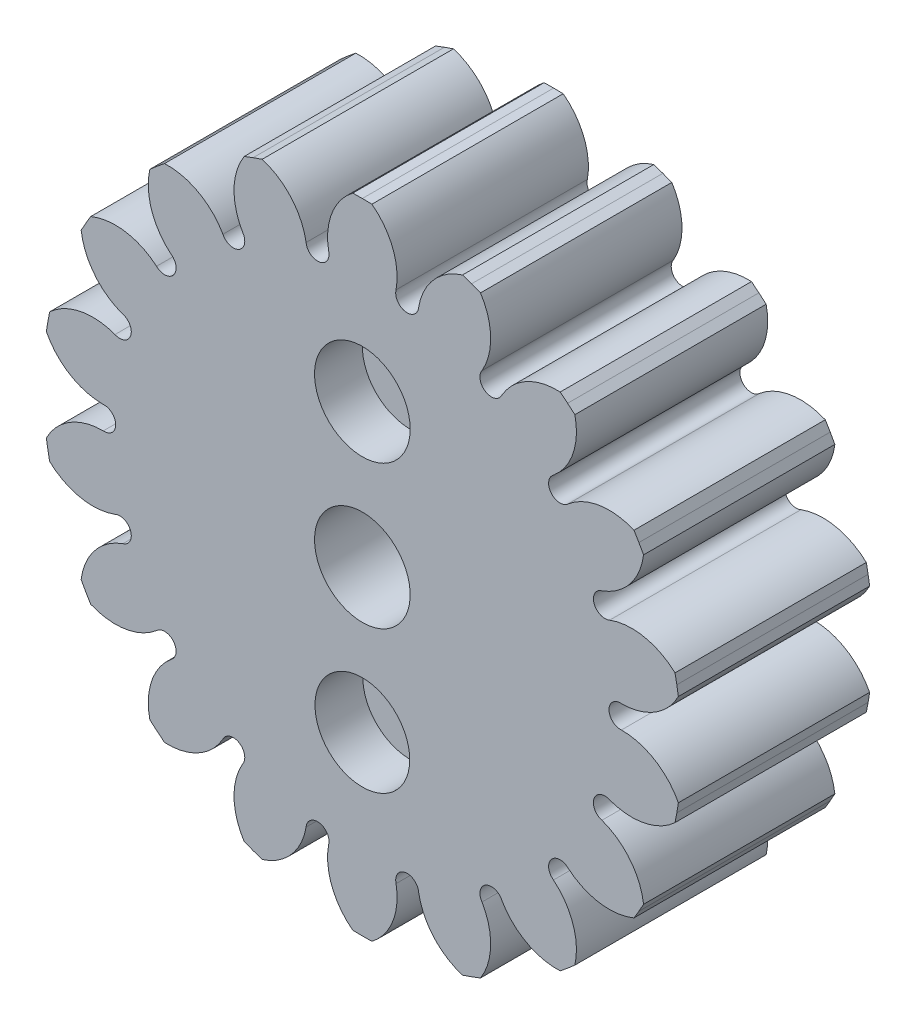
SolidWorks part; units mm, degrees
ref_plane "Front Plane" through (0, 0, 0) normal (0, 0, 1) x (1, 0, 0)
ref_plane "Top Plane" through (0, 0, 0) normal (0, 1, 0) x (1, 0, 0)
ref_plane "Right Plane" through (0, 0, 0) normal (1, 0, 0) x (0, 0, -1)
sketch "Sketch1" plane through (0, 0, 0) normal (0, 0, 1) x (1, 0, 0)
  line L0 (0, 42.401) -> (0, 0) construction
  line L1 (0, 42.401) -> (-1.27, 42.382)
  line L2 (0, 42.401) -> (1.27, 42.382)
  line L3 (14.502, 39.8439) -> (13.3021, 40.2604)
  line L4 (14.502, 39.8439) -> (15.6889, 39.3916)
  line L5 (27.2548, 32.481) -> (26.2697, 33.2828)
  line L6 (27.2548, 32.481) -> (28.2155, 31.6501)
  line L7 (36.7203, 21.2005) -> (36.0689, 22.2908)
  line L8 (36.7203, 21.2005) -> (37.3389, 20.0911)
  line L9 (41.7568, 7.3629) -> (41.5175, 8.6103)
  line L10 (41.7568, 7.3629) -> (41.9586, 6.1088)
  line L11 (41.7568, -7.3629) -> (41.9586, -6.1088)
  line L12 (41.7568, -7.3629) -> (41.5175, -8.6103)
  line L13 (36.7203, -21.2005) -> (37.3389, -20.0911)
  line L14 (36.7203, -21.2005) -> (36.0689, -22.2908)
  line L15 (27.2548, -32.481) -> (28.2155, -31.6501)
  line L16 (27.2548, -32.481) -> (26.2697, -33.2828)
  line L17 (14.502, -39.8439) -> (15.6889, -39.3916)
  line L18 (14.502, -39.8439) -> (13.3021, -40.2604)
  line L19 (0, -42.401) -> (1.27, -42.382)
  line L20 (0, -42.401) -> (-1.27, -42.382)
  line L21 (-14.502, -39.8439) -> (-13.3021, -40.2604)
  line L22 (-14.502, -39.8439) -> (-15.6889, -39.3916)
  line L23 (-27.2548, -32.481) -> (-26.2697, -33.2828)
  line L24 (-27.2548, -32.481) -> (-28.2155, -31.6501)
  line L25 (-36.7203, -21.2005) -> (-36.0689, -22.2908)
  line L26 (-36.7203, -21.2005) -> (-37.3389, -20.0911)
  line L27 (-41.7568, -7.3629) -> (-41.5175, -8.6103)
  line L28 (-41.7568, -7.3629) -> (-41.9586, -6.1088)
  line L29 (-41.7568, 7.3629) -> (-41.9586, 6.1088)
  line L30 (-41.7568, 7.3629) -> (-41.5175, 8.6103)
  line L31 (-36.7203, 21.2005) -> (-37.3389, 20.0911)
  line L32 (-36.7203, 21.2005) -> (-36.0689, 22.2908)
  line L33 (-27.2548, 32.481) -> (-28.2155, 31.6501)
  line L34 (-27.2548, 32.481) -> (-26.2697, 33.2828)
  line L35 (-14.502, 39.8439) -> (-15.6889, 39.3916)
  line L36 (-14.502, 39.8439) -> (-13.3021, 40.2604)
  circle A0 centre (0, 0) radius 32.749
  circle A1 centre (0, 0) radius 42.401
  arc A3 (4.4777, 34.1403) -> (5.6868, 32.2515) centre (5.9514, 33.7523) ccw
  arc A5 (4.4777, 34.1403) -> (1.27, 42.382) centre (-3.8295, 35.6522) ccw
  arc A6 (-4.4777, 34.1403) -> (-5.6868, 32.2515) centre (-5.9514, 33.7523) cw
  arc A7 (-4.4777, 34.1403) -> (-1.27, 42.382) centre (3.8295, 35.6522) cw
  arc A8 (15.8843, 30.5499) -> (15.6889, 39.3916) centre (8.5952, 34.8119) ccw
  arc A9 (7.469, 33.6128) -> (13.3021, 40.2604) centre (15.7923, 32.1923) cw
  arc A10 (7.469, 33.6128) -> (5.6868, 32.2515) centre (5.9514, 33.7523) cw
  arc A11 (15.8843, 30.5499) -> (16.3745, 28.3615) centre (17.1365, 29.6813) ccw
  arc A12 (25.375, 23.2748) -> (28.2155, 31.6501) centre (19.9832, 29.7727) ccw
  arc A13 (18.5149, 29.0312) -> (26.2697, 33.2828) centre (25.8504, 24.8496) cw
  arc A14 (18.5149, 29.0312) -> (16.3745, 28.3615) centre (17.1365, 29.6813) cw
  arc A15 (25.375, 23.2748) -> (25.0872, 21.0506) centre (26.2546, 22.0302) ccw
  arc A16 (31.8052, 13.1924) -> (37.3389, 20.0911) centre (28.961, 21.1425) ccw
  arc A17 (27.3275, 20.9479) -> (36.0689, 22.2908) centre (32.7905, 14.5097) cw
  arc A18 (27.3275, 20.9479) -> (25.0872, 21.0506) centre (26.2546, 22.0302) cw
  arc A19 (31.8052, 13.1924) -> (30.774, 11.2008) centre (32.2061, 11.7221) ccw
  arc A20 (34.3992, 1.5188) -> (41.9586, 6.1088) centre (34.4456, 9.9623) ccw
  arc A21 (32.8441, 10.338) -> (41.5175, 8.6103) centre (35.7755, 2.4196) cw
  arc A22 (32.8441, 10.338) -> (30.774, 11.2008) centre (32.2061, 11.7221) cw
  arc A23 (34.3992, 1.5188) -> (32.749, 0) centre (34.273, 0) ccw
  arc A24 (32.8441, -10.338) -> (41.5175, -8.6103) centre (35.7755, -2.4196) ccw
  arc A25 (34.3992, -1.5188) -> (41.9586, -6.1088) centre (34.4456, -9.9623) cw
  arc A26 (34.3992, -1.5188) -> (32.749, 0) centre (34.273, 0) cw
  arc A27 (32.8441, -10.338) -> (30.774, -11.2008) centre (32.2061, -11.7221) ccw
  arc A28 (27.3275, -20.9479) -> (36.0689, -22.2908) centre (32.7905, -14.5097) ccw
  arc A29 (31.8052, -13.1924) -> (37.3389, -20.0911) centre (28.961, -21.1425) cw
  arc A30 (31.8052, -13.1924) -> (30.774, -11.2008) centre (32.2061, -11.7221) cw
  arc A31 (27.3275, -20.9479) -> (25.0872, -21.0506) centre (26.2546, -22.0302) ccw
  arc A32 (18.5149, -29.0312) -> (26.2697, -33.2828) centre (25.8504, -24.8496) ccw
  arc A33 (25.375, -23.2748) -> (28.2155, -31.6501) centre (19.9832, -29.7727) cw
  arc A34 (25.375, -23.2748) -> (25.0872, -21.0506) centre (26.2546, -22.0302) cw
  arc A35 (18.5149, -29.0312) -> (16.3745, -28.3615) centre (17.1365, -29.6813) ccw
  arc A36 (7.469, -33.6128) -> (13.3021, -40.2604) centre (15.7923, -32.1923) ccw
  arc A37 (15.8843, -30.5499) -> (15.6889, -39.3916) centre (8.5952, -34.8119) cw
  arc A38 (15.8843, -30.5499) -> (16.3745, -28.3615) centre (17.1365, -29.6813) cw
  arc A39 (7.469, -33.6128) -> (5.6868, -32.2515) centre (5.9514, -33.7523) ccw
  arc A40 (-4.4777, -34.1403) -> (-1.27, -42.382) centre (3.8295, -35.6522) ccw
  arc A41 (4.4777, -34.1403) -> (1.27, -42.382) centre (-3.8295, -35.6522) cw
  arc A42 (4.4777, -34.1403) -> (5.6868, -32.2515) centre (5.9514, -33.7523) cw
  arc A43 (-4.4777, -34.1403) -> (-5.6868, -32.2515) centre (-5.9514, -33.7523) ccw
  arc A44 (-15.8843, -30.5499) -> (-15.6889, -39.3916) centre (-8.5952, -34.8119) ccw
  arc A45 (-7.469, -33.6128) -> (-13.3021, -40.2604) centre (-15.7923, -32.1923) cw
  arc A46 (-7.469, -33.6128) -> (-5.6868, -32.2515) centre (-5.9514, -33.7523) cw
  arc A47 (-15.8843, -30.5499) -> (-16.3745, -28.3615) centre (-17.1365, -29.6813) ccw
  arc A48 (-25.375, -23.2748) -> (-28.2155, -31.6501) centre (-19.9832, -29.7727) ccw
  arc A49 (-18.5149, -29.0312) -> (-26.2697, -33.2828) centre (-25.8504, -24.8496) cw
  arc A50 (-18.5149, -29.0312) -> (-16.3745, -28.3615) centre (-17.1365, -29.6813) cw
  arc A51 (-25.375, -23.2748) -> (-25.0872, -21.0506) centre (-26.2546, -22.0302) ccw
  arc A52 (-31.8052, -13.1924) -> (-37.3389, -20.0911) centre (-28.961, -21.1425) ccw
  arc A53 (-27.3275, -20.9479) -> (-36.0689, -22.2908) centre (-32.7905, -14.5097) cw
  arc A54 (-27.3275, -20.9479) -> (-25.0872, -21.0506) centre (-26.2546, -22.0302) cw
  arc A55 (-31.8052, -13.1924) -> (-30.774, -11.2008) centre (-32.2061, -11.7221) ccw
  arc A56 (-34.3992, -1.5188) -> (-41.9586, -6.1088) centre (-34.4456, -9.9623) ccw
  arc A57 (-32.8441, -10.338) -> (-41.5175, -8.6103) centre (-35.7755, -2.4196) cw
  arc A58 (-32.8441, -10.338) -> (-30.774, -11.2008) centre (-32.2061, -11.7221) cw
  arc A59 (-34.3992, -1.5188) -> (-32.749, 0) centre (-34.273, 0) ccw
  arc A60 (-32.8441, 10.338) -> (-41.5175, 8.6103) centre (-35.7755, 2.4196) ccw
  arc A61 (-34.3992, 1.5188) -> (-41.9586, 6.1088) centre (-34.4456, 9.9623) cw
  arc A62 (-34.3992, 1.5188) -> (-32.749, 0) centre (-34.273, 0) cw
  arc A63 (-32.8441, 10.338) -> (-30.774, 11.2008) centre (-32.2061, 11.7221) ccw
  arc A64 (-27.3275, 20.9479) -> (-36.0689, 22.2908) centre (-32.7905, 14.5097) ccw
  arc A65 (-31.8052, 13.1924) -> (-37.3389, 20.0911) centre (-28.961, 21.1425) cw
  arc A66 (-31.8052, 13.1924) -> (-30.774, 11.2008) centre (-32.2061, 11.7221) cw
  arc A67 (-27.3275, 20.9479) -> (-25.0872, 21.0506) centre (-26.2546, 22.0302) ccw
  arc A68 (-18.5149, 29.0312) -> (-26.2697, 33.2828) centre (-25.8504, 24.8496) ccw
  arc A69 (-25.375, 23.2748) -> (-28.2155, 31.6501) centre (-19.9832, 29.7727) cw
  arc A70 (-25.375, 23.2748) -> (-25.0872, 21.0506) centre (-26.2546, 22.0302) cw
  arc A71 (-18.5149, 29.0312) -> (-16.3745, 28.3615) centre (-17.1365, 29.6813) ccw
  arc A72 (-7.469, 33.6128) -> (-13.3021, 40.2604) centre (-15.7923, 32.1923) ccw
  arc A73 (-15.8843, 30.5499) -> (-15.6889, 39.3916) centre (-8.5952, 34.8119) cw
  arc A74 (-15.8843, 30.5499) -> (-16.3745, 28.3615) centre (-17.1365, 29.6813) cw
  arc A75 (-7.469, 33.6128) -> (-5.6868, 32.2515) centre (-5.9514, 33.7523) ccw
  point P6 (0, 0)
  point P12 (0, 0)
  point P14 (-16.0502, 28.5462)
  point P206 (0, 0)
  point P207 (0, 0)
  point P208 (0, 0)
  dimension "D3" = 9.652
  dimension "D6" = 3.048
  dimension "D4" = 18
  dimension "D5" = 1.27
extrude "Boss-Extrude1" add sketch "Sketch1" along normal blind 25.4
sketch "Sketch2" plane through (0, 0, 25.4) normal (0, 0, 1) x (1, 0, 0)
  circle A0 centre (0, 0) radius 6.35
  circle A1 centre (0, 0) radius 12.7
  circle A2 centre (0, 0) radius 25.4
  circle A5 centre (0, 19.05) radius 6.35
  circle A6 centre (0, -18.9894) radius 6.2894
  dimension "D1" = 12.7
  dimension "D2" = 25.4
  dimension "D3" = 50.8
extrude "Cut-Extrude1" cut sketch "Sketch2" against normal blind 6.35 contours A5 | A6
ref_plane "Plane1" through (0, 0, 12.7) normal (0, 0, 1) x (1, 0, 0)
mirror "Mirror2" about plane through (0, 0, 12.7) normal (0, 0, 1) of "Cut-Extrude1"
sketch "Sketch3" plane through (0, 0, 0) normal (0, 0, -1) x (-1, 0, 0)
  circle A0 centre (0, 0) radius 6.35
  dimension "D1" = 12.7
extrude "Cut-Extrude2" cut sketch "Sketch3" against normal through all
